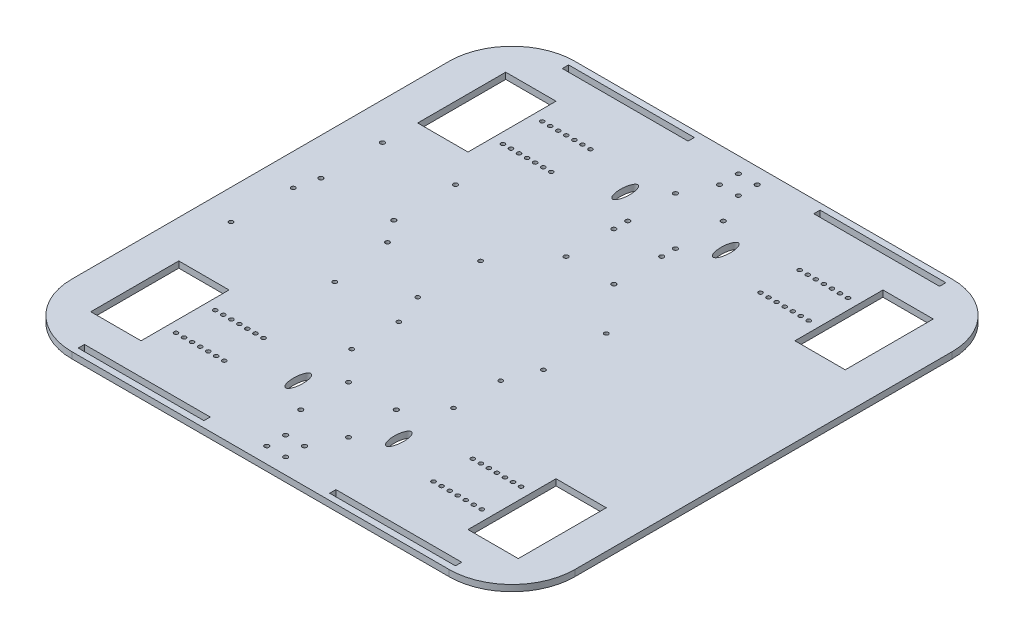
SolidWorks part; units mm, degrees
ref_plane "Front Plane" through (0, 0, 0) normal (0, 0, 1) x (1, 0, 0)
ref_plane "Top Plane" through (0, 0, 0) normal (0, 1, 0) x (1, 0, 0)
ref_plane "Right Plane" through (0, 0, 0) normal (1, 0, 0) x (0, 0, -1)
sketch "Sketch1" plane through (0, 0, 0) normal (0, 1, 0) x (1, 0, 0)
  line L0 (0, -1000) -> (0, 49000) construction
  line L1 (-170, 165) -> (-130, 165)
  line L2 (-170, 165) -> (-170, 95)
  line L3 (-170, 95) -> (-130, 95)
  line L4 (-130, 165) -> (-130, 95)
  line L5 (170, 95) -> (130, 95)
  line L6 (130, 165) -> (130, 95)
  line L7 (170, 165) -> (130, 165)
  line L8 (170, 165) -> (170, 95)
  line L9 (-1000, 0) -> (49000, 0) construction
  line L10 (-10, 190) -> (10, 190)
  line L11 (-10, 190) -> (-10, 170)
  line L12 (-10, 170) -> (10, 170)
  line L13 (10, 190) -> (10, 170)
  line L14 (-1010, 180) -> (48990, 180) construction
  line L15 (-1010, -180) -> (48990, -180) construction
  line L16 (0, 1000) -> (0, -49000) construction
  line L17 (-10, -170) -> (10, -170)
  line L18 (10, -190) -> (10, -170)
  line L19 (-10, -190) -> (10, -190)
  line L20 (-10, -190) -> (-10, -170)
  line L21 (170, -165) -> (170, -95)
  line L22 (-200, 200) -> (200, 200)
  line L23 (-200, 200) -> (-200, -200)
  line L24 (-200, -200) -> (200, -200)
  line L25 (200, 200) -> (200, -200)
  line L26 (170, -165) -> (130, -165)
  line L27 (130, -165) -> (130, -95)
  line L28 (170, -95) -> (130, -95)
  line L29 (-170, -95) -> (-130, -95)
  line L30 (-130, -165) -> (-130, -95)
  line L31 (-170, -165) -> (-130, -165)
  line L32 (-170, -165) -> (-170, -95)
  circle A0 centre (0, 0) radius 200 construction
  circle A1 centre (-7.5, 187.5) radius 1.75
  circle A2 centre (7.5, 187.5) radius 1.75
  circle A3 centre (7.5, 172.5) radius 1.75
  circle A4 centre (-7.5, 172.5) radius 1.75
  circle A5 centre (7.5, -187.5) radius 1.75
  circle A6 centre (-7.5, -187.5) radius 1.75
  circle A7 centre (-7.5, -172.5) radius 1.75
  circle A8 centre (7.5, -172.5) radius 1.75
  point P8 (-150, 165)
  point P19 (0, 190)
  point P22 (-10, 180)
  dimension "D1" = 400
  dimension "D7" = 3.5
  dimension "D2" = 40
  dimension "D3" = 70
  dimension "D4" = 150
  dimension "D5" = 20
  dimension "D6" = 180
  dimension "D8" = 2.5
  dimension "D9" = 2.5
  dimension "D10" = 35
extrude "Boss-Extrude2" add sketch "Sketch1" along normal blind 5 contours L25 L22 L23 L24 L1 L4 L3 L2 L7 L8 L5 L6 L10 L13 L12 L11 L19 L20 L17 L18 | L20 L19 L18 L17 A6 A5 A7 A8 | L13 L10 L11 L12 A2 A1 A3 A4
fillet "Fillet1" radius 50 4 edges at (200, 2.5, -200) (200, 2.5, 200) (-200, 2.5, 200) (-200, 2.5, -200)
sketch "Sketch2" plane through (0, 5, 0) normal (0, 1, 0) x (1, 0, 0)
  line L0 (-1094.0419, 130) -> (48905.9581, 130) construction
  line L1 (-130, 148.8) -> (-78.5, 148.8) construction
  line L2 (-130, 148.8) -> (-130, 111.2) construction
  line L3 (-130, 111.2) -> (-78.5, 111.2) construction
  line L4 (-78.5, 148.8) -> (-78.5, 111.2) construction
  line L5 (-130, 165) -> (-130, 95) construction
  line L6 (-170, 165) -> (-170, 95) construction
  line L7 (0, -1000) -> (0, 49000) construction
  line L8 (130, 111.2) -> (78.5, 111.2) construction
  line L9 (78.5, 148.8) -> (78.5, 111.2) construction
  line L10 (130, 148.8) -> (78.5, 148.8) construction
  line L11 (130, 148.8) -> (130, 111.2) construction
  line L12 (-1000, 0) -> (49000, 0) construction
  line L13 (130, -148.8) -> (130, -111.2) construction
  line L14 (130, -148.8) -> (78.5, -148.8) construction
  line L15 (78.5, -148.8) -> (78.5, -111.2) construction
  line L16 (130, -111.2) -> (78.5, -111.2) construction
  line L17 (-78.5, -148.8) -> (-78.5, -111.2) construction
  line L18 (-130, -111.2) -> (-78.5, -111.2) construction
  line L19 (-130, -148.8) -> (-130, -111.2) construction
  line L20 (-130, -148.8) -> (-78.5, -148.8) construction
  line L21 (-1094.0419, -130) -> (48905.9581, -130) construction
  circle A0 centre (-121.6, 145.6) radius 1.6
  circle A1 centre (-115.2, 145.6) radius 1.6
  circle A2 centre (-108.8, 145.6) radius 1.6
  circle A3 centre (-102.4, 145.6) radius 1.6
  circle A4 centre (-96, 145.6) radius 1.6
  circle A5 centre (-89.6, 145.6) radius 1.6
  circle A6 centre (-83.2, 145.6) radius 1.6
  circle A7 centre (-83.2, 114.4) radius 1.6
  circle A8 centre (-89.6, 114.4) radius 1.6
  circle A9 centre (-96, 114.4) radius 1.6
  circle A10 centre (-102.4, 114.4) radius 1.6
  circle A11 centre (-108.8, 114.4) radius 1.6
  circle A12 centre (-115.2, 114.4) radius 1.6
  circle A13 centre (-121.6, 114.4) radius 1.6
  circle A14 centre (83.2, 114.4) radius 1.6
  circle A15 centre (89.6, 114.4) radius 1.6
  circle A16 centre (96, 114.4) radius 1.6
  circle A17 centre (102.4, 114.4) radius 1.6
  circle A18 centre (108.8, 114.4) radius 1.6
  circle A19 centre (115.2, 114.4) radius 1.6
  circle A20 centre (121.6, 114.4) radius 1.6
  circle A21 centre (83.2, 145.6) radius 1.6
  circle A22 centre (89.6, 145.6) radius 1.6
  circle A23 centre (96, 145.6) radius 1.6
  circle A24 centre (102.4, 145.6) radius 1.6
  circle A25 centre (108.8, 145.6) radius 1.6
  circle A26 centre (115.2, 145.6) radius 1.6
  circle A27 centre (121.6, 145.6) radius 1.6
  circle A28 centre (121.6, -145.6) radius 1.6
  circle A29 centre (115.2, -145.6) radius 1.6
  circle A30 centre (108.8, -145.6) radius 1.6
  circle A31 centre (102.4, -145.6) radius 1.6
  circle A32 centre (96, -145.6) radius 1.6
  circle A33 centre (89.6, -145.6) radius 1.6
  circle A34 centre (83.2, -145.6) radius 1.6
  circle A35 centre (121.6, -114.4) radius 1.6
  circle A36 centre (115.2, -114.4) radius 1.6
  circle A37 centre (108.8, -114.4) radius 1.6
  circle A38 centre (102.4, -114.4) radius 1.6
  circle A39 centre (96, -114.4) radius 1.6
  circle A40 centre (89.6, -114.4) radius 1.6
  circle A41 centre (83.2, -114.4) radius 1.6
  circle A42 centre (-121.6, -114.4) radius 1.6
  circle A43 centre (-115.2, -114.4) radius 1.6
  circle A44 centre (-108.8, -114.4) radius 1.6
  circle A45 centre (-102.4, -114.4) radius 1.6
  circle A46 centre (-96, -114.4) radius 1.6
  circle A47 centre (-89.6, -114.4) radius 1.6
  circle A48 centre (-83.2, -114.4) radius 1.6
  circle A49 centre (-83.2, -145.6) radius 1.6
  circle A50 centre (-89.6, -145.6) radius 1.6
  circle A51 centre (-96, -145.6) radius 1.6
  circle A52 centre (-102.4, -145.6) radius 1.6
  circle A53 centre (-108.8, -145.6) radius 1.6
  circle A54 centre (-115.2, -145.6) radius 1.6
  circle A55 centre (-121.6, -145.6) radius 1.6
  point P9 (-130, 130)
  point P40 (-170, 130)
  dimension "D3" = 3.2
  dimension "D7" = 6.4
  dimension "D5" = 8.4
  dimension "D1" = 37.6
  dimension "D2" = 4.7
  dimension "D4" = 31.2
  dimension "D6" = 7
extrude "Cut-Extrude1" cut sketch "Sketch2" against normal blind 5
sketch "Sketch3" plane through (0, 5, 0) normal (0, 1, 0) x (1, 0, 0)
  line L0 (-150, -200) -> (150, -200) construction
  line L1 (-190, 3.34) -> (-88.4, 3.34) construction
  line L2 (-190, 3.34) -> (-190, -50) construction
  line L3 (-190, -50) -> (-88.4, -50) construction
  line L4 (-88.4, 3.34) -> (-88.4, -50) construction
  line L5 (-200, 150) -> (-200, -150) construction
  circle A0 centre (-176.03, -47.46) radius 1.65
  circle A1 centre (-174.76, 0.8) radius 1.65
  circle A2 centre (-93.48, -47.46) radius 1.65
  circle A3 centre (-99.83, 0.8) radius 1.65
  dimension "D5" = 3.3
  dimension "D8" = 3.3
  dimension "D9" = 96.52
  dimension "D10" = 90.17
  dimension "D1" = 101.6
  dimension "D2" = 53.34
  dimension "D3" = 13.97
  dimension "D4" = 2.54
  dimension "D6" = 15.24
  dimension "D7" = 50.8
  dimension "D11" = 150
  dimension "D12" = 10
extrude "Cut-Extrude2" cut sketch "Sketch3" against normal blind 10 contours A1 | A2 | L2 L1 L4 L3 | A0 | A3
sketch "Sketch4" plane through (0, 5, 0) normal (0, 1, 0) x (1, 0, 0)
  line L0 (-19, 149) -> (19, 149) construction
  line L1 (-1149.7342, 130) -> (48850.2658, 130) construction
  line L2 (-22, 152) -> (22, 152) construction
  line L3 (-22, 152) -> (-22, 108) construction
  line L4 (-22, 108) -> (22, 108) construction
  line L5 (22, 152) -> (22, 108) construction
  line L6 (-19, 111) -> (19, 111) construction
  line L7 (-19, 100) -> (19, 100) construction
  line L8 (-1231.3219, 81) -> (48768.6781, 81) construction
  line L9 (-22, 103) -> (22, 103) construction
  line L10 (-22, 103) -> (-22, 59) construction
  line L11 (-22, 59) -> (22, 59) construction
  line L12 (22, 103) -> (22, 59) construction
  line L13 (-19, 62) -> (19, 62) construction
  line L14 (-19, -149) -> (19, -149) construction
  line L15 (-22, -152) -> (22, -152) construction
  line L16 (-130, 165) -> (-130, 95) construction
  line L17 (-150, 200) -> (150, 200) construction
  line L18 (22, -108) -> (22, -152) construction
  line L19 (-22, -108) -> (-22, -152) construction
  line L20 (-19, -111) -> (19, -111) construction
  line L21 (-22, -108) -> (22, -108) construction
  line L22 (-1022, -130) -> (48978, -130) construction
  line L23 (-130, -165) -> (-130, -95) construction
  circle A0 centre (-19, 149) radius 1.75
  circle A1 centre (19, 149) radius 1.75
  circle A2 centre (19, 111) radius 1.75
  circle A3 centre (-19, 111) radius 1.75
  circle A4 centre (-19, 100) radius 1.75
  circle A5 centre (19, 100) radius 1.75
  circle A6 centre (19, 62) radius 1.75
  circle A7 centre (-19, 62) radius 1.75
  circle A8 centre (-19, -149) radius 1.75
  circle A9 centre (19, -149) radius 1.75
  circle A10 centre (-19, -111) radius 1.75
  circle A11 centre (19, -111) radius 1.75
  point P9 (0, 149)
  point P10 (0, 152)
  point P14 (-22, 130)
  point P26 (0, 100)
  point P27 (0, 103)
  point P31 (-22, 81)
  point P38 (-130, 130)
  point P39 (0, 200)
  point P40 (0, 108)
  point P56 (-22, -130)
  point P58 (-130, -130)
  dimension "D1" = 3.5
  dimension "D5" = 3.5
  dimension "D2" = 38
  dimension "D3" = 44
  dimension "D4" = 38
  dimension "D6" = 38
  dimension "D7" = 44
  dimension "D8" = 38
  dimension "D9" = 5
  dimension "D10" = 2
extrude "Cut-Extrude3" cut sketch "Sketch4" against normal blind 10
sketch "Sketch5" plane through (0, 5, 0) normal (0, 1, 0) x (1, 0, 0)
  line L0 (-1136.3236, 43) -> (48863.6764, 43) construction
  line L1 (-174, 15) -> (-89, 15) construction
  line L2 (-174, 15) -> (-174, 71) construction
  line L3 (-174, 71) -> (-89, 71) construction
  line L4 (-89, 15) -> (-89, 71) construction
  line L5 (-180, 10) -> (-83, 10) construction
  line L6 (-180, 10) -> (-180, 76) construction
  line L7 (-180, 76) -> (-83, 76) construction
  line L8 (-83, 10) -> (-83, 76) construction
  line L9 (-200, 150) -> (-200, -150) construction
  line L10 (-150, -200) -> (150, -200) construction
  circle A0 centre (-170.5, 67.5) radius 1.75
  circle A1 centre (-112.5, 67.5) radius 1.75
  circle A2 centre (-112.5, 18.5) radius 1.75
  circle A3 centre (-170.5, 18.5) radius 1.75
  dimension "D4" = 3.5
  dimension "D5" = 3.5
  dimension "D1" = 56
  dimension "D2" = 85
  dimension "D3" = 58
  dimension "D6" = 3.5
  dimension "D7" = 49
  dimension "D8" = 3.5
  dimension "D9" = 5
  dimension "D10" = 5
  dimension "D11" = 6
  dimension "D12" = 6
  dimension "D13" = 20
  dimension "D14" = 210
extrude "Cut-Extrude4" cut sketch "Sketch5" against normal blind 10
sketch "Sketch6" plane through (0, 5, 0) normal (0, 1, 0) x (1, 0, 0)
  line L0 (-130, 165) -> (-130, 95) construction
  line L1 (0, -800) -> (0, 49200) construction
  line L2 (-150, 200) -> (150, 200) construction
  line L3 (-1200, 0) -> (48800, 0) construction
  line L4 (-200, 150) -> (-200, -150) construction
  ellipse E0 centre (-40, 130) end of major axis (-40, 140) minor radius 3.75
  ellipse E1 centre (40, 130) end of major axis (40, 140) minor radius 3.75
  ellipse E2 centre (40, -130) end of major axis (40, -140) minor radius 3.75
  ellipse E3 centre (-40, -130) end of major axis (-40, -140) minor radius 3.75
  point P13 (-130, 130)
  point P14 (-200, 0)
  point P26 (0, 200)
  dimension "D1" = 90
  dimension "D2" = 20
  dimension "D3" = 7.5
extrude "Cut-Extrude5" cut sketch "Sketch6" against normal blind 10
sketch "Sketch7" plane through (0, 5, 0) normal (0, 1, 0) x (1, 0, 0)
  line L0 (0, -1008.1082) -> (0, 48991.8918) construction
  line L1 (-53, 28) -> (53, 28) construction
  line L2 (-53, 28) -> (-53, -28) construction
  line L3 (-53, -28) -> (53, -28) construction
  line L4 (53, 28) -> (53, -28) construction
  line L5 (-53, 28) -> (-47, 28) construction
  line L6 (-53, 28) -> (-53, 22) construction
  line L7 (-53, 22) -> (-47, 22) construction
  line L8 (-47, 28) -> (-47, 22) construction
  line L9 (-1053, 0) -> (48947, 0) construction
  line L10 (-150, -200) -> (150, -200) construction
  line L11 (-200, 150) -> (-200, -150) construction
  circle A1 centre (-50, 25) radius 1.65
  circle A2 centre (50, 25) radius 1.65
  circle A3 centre (50, -25) radius 1.65
  circle A4 centre (-50, -25) radius 1.65
  point P10 (-50, 22)
  point P15 (-47, 25)
  point P16 (0, 28)
  point P17 (-53, 0)
  point P25 (0, -200)
  point P28 (-200, 0)
  dimension "D3" = 3.3
  dimension "D1" = 106
  dimension "D2" = 56
  dimension "D5" = 6
  dimension "D6" = 6
extrude "Cut-Extrude6" cut sketch "Sketch7" against normal blind 10
sketch "Sketch8" plane through (0, 5, 0) normal (0, 1, 0) x (1, 0, 0)
  line L0 (0, -1046.6714) -> (0, 48953.3286) construction
  line L1 (-43.5, -46.5) -> (43.5, -46.5) construction
  line L2 (-43.5, -46.5) -> (-43.5, -90) construction
  line L3 (-43.5, -90) -> (43.5, -90) construction
  line L4 (43.5, -46.5) -> (43.5, -90) construction
  line L5 (-43.5, -46.5) -> (-37.5, -46.5) construction
  line L6 (-43.5, -46.5) -> (-43.5, -52.5) construction
  line L7 (-43.5, -52.5) -> (-37.5, -52.5) construction
  line L8 (-37.5, -46.5) -> (-37.5, -52.5) construction
  line L9 (-1043.5, -68.25) -> (48956.5, -68.25) construction
  line L10 (37.5, -46.5) -> (37.5, -52.5) construction
  line L11 (43.5, -52.5) -> (37.5, -52.5) construction
  line L12 (-150, -200) -> (150, -200) construction
  circle A0 centre (-40.5, -49.5) radius 1.65
  circle A1 centre (40.5, -49.5) radius 1.65
  circle A2 centre (40.5, -87) radius 1.65
  circle A3 centre (-40.5, -87) radius 1.65
  point P10 (-40.5, -52.5)
  point P11 (-37.5, -49.5)
  point P15 (0, -46.5)
  point P17 (-43.5, -68.25)
  point P28 (0, -200)
  dimension "D3" = 3.3
  dimension "D1" = 87
  dimension "D2" = 6
  dimension "D4" = 43.5
  dimension "D5" = 110
extrude "Cut-Extrude7" cut sketch "Sketch8" against normal blind 5
sketch "Sketch9" plane through (0, 5, 0) normal (0, 1, 0) x (1, 0, 0)
  line L0 (-150, 200) -> (150, 200) construction
  line L1 (-150, 195) -> (-50, 195)
  line L2 (-150, 195) -> (-150, 190)
  line L3 (-150, 190) -> (-50, 190)
  line L4 (-50, 195) -> (-50, 190)
  line L5 (0, -800) -> (0, 49200) construction
  line L6 (150, 190) -> (50, 190)
  line L7 (50, 195) -> (50, 190)
  line L8 (150, 195) -> (50, 195)
  line L9 (150, 195) -> (150, 190)
  line L10 (-1200, 0) -> (48800, 0) construction
  line L11 (-200, 150) -> (-200, -150) construction
  line L12 (150, -195) -> (150, -190)
  line L13 (150, -195) -> (50, -195)
  line L14 (50, -195) -> (50, -190)
  line L15 (150, -190) -> (50, -190)
  line L16 (-150, -190) -> (-50, -190)
  line L17 (-50, -195) -> (-50, -190)
  line L18 (-150, -195) -> (-50, -195)
  line L19 (-150, -195) -> (-150, -190)
  point P13 (0, 200)
  point P22 (-200, 0)
  dimension "D1" = 5
  dimension "D2" = 5
  dimension "D3" = 100
extrude "Cut-Extrude8" cut sketch "Sketch9" against normal blind 10
